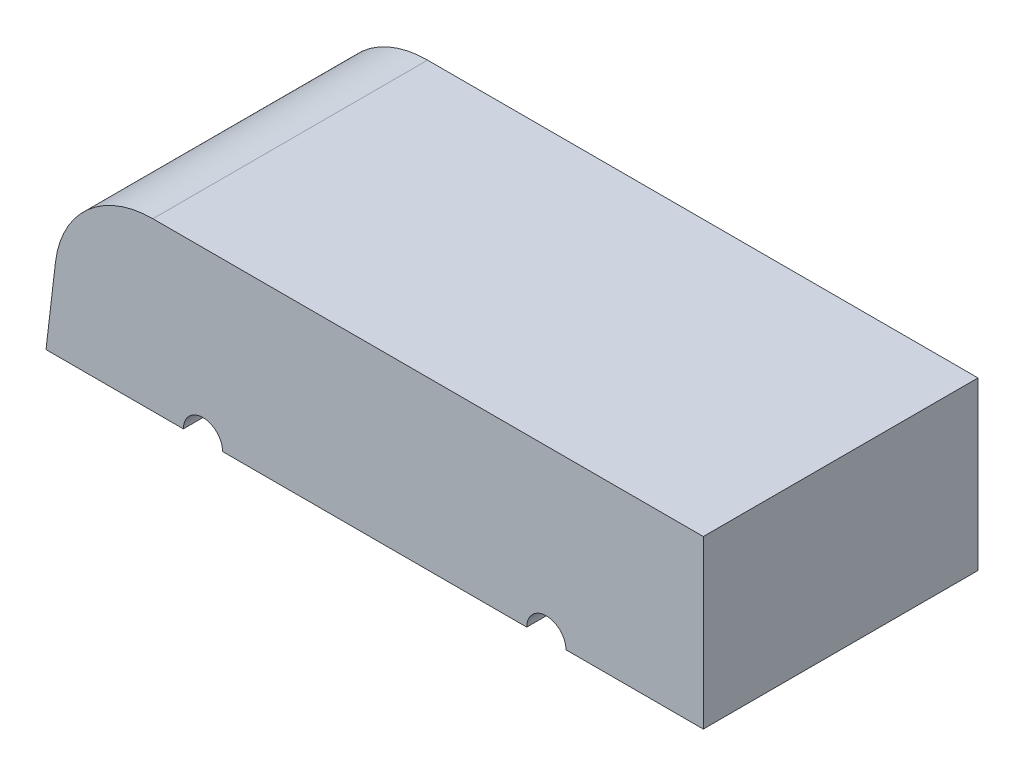
SolidWorks part; units mm, degrees
material "Brass"
ref_plane "Front Plane" through (0, 0, 0) normal (0, 0, 1) x (1, 0, 0)
ref_plane "Top Plane" through (0, 0, 0) normal (0, 1, 0) x (1, 0, 0)
ref_plane "Right Plane" through (0, 0, 0) normal (1, 0, 0) x (0, 0, -1)
sketch "Sketch1" plane through (0, 0, 0) normal (0, 0, 1) x (1, 0, 0)
  line L1 (85.09, 0) -> (85.09, 21.59)
  line L2 (85.09, 21.59) -> (2.54, 21.59)
  line L3 (2.54, 21.59) -> (0, 0)
  line L4 (0, 0) -> (17.78, 0)
  line L5 (22.86, 0) -> (62.23, 0)
  line L6 (67.31, 0) -> (85.09, 0)
  arc A0 (17.78, 0) -> (22.86, 0) centre (20.32, 0) cw
  arc A1 (62.23, 0) -> (67.31, 0) centre (64.77, 0) cw
  point P3 (20.32, 0)
  point P6 (64.77, 0)
  dimension "D1" = 20.32
  dimension "D2" = 20.32
  dimension "D3" = 82.55
  dimension "D4" = 85.09
  dimension "D5" = 21.59
extrude "Boss-Extrude1" add sketch "Sketch1" along normal blind 35.56
ref_plane "Plane1" through (0, 0, 0) normal (0, 0, -1) x (-1, 0, 0)
fillet "Fillet1" radius 12.7 1 edges at (2.54, 21.59, 17.78)
